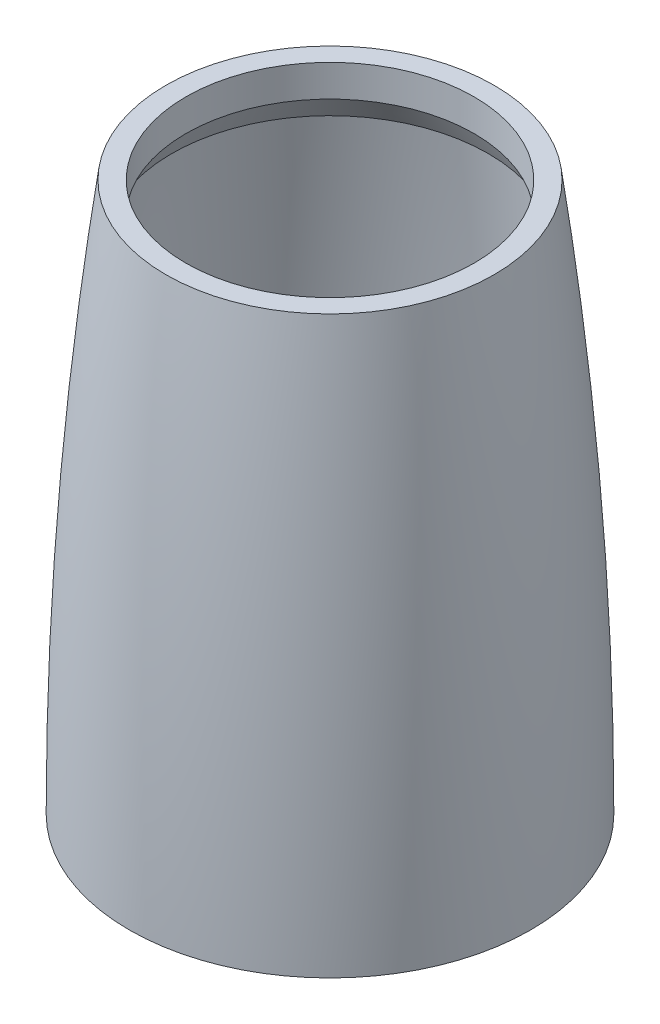
SolidWorks part; units mm, degrees
ref_plane "Front Plane" through (0, 0, 0) normal (0, 0, 1) x (1, 0, 0)
ref_plane "Top Plane" through (0, 0, 0) normal (0, 1, 0) x (1, 0, 0)
ref_plane "Right Plane" through (0, 0, 0) normal (1, 0, 0) x (0, 0, -1)
sketch "Sketch1" plane through (0, 0, 0) normal (1, 0, 0) x (0, 0, -1)
  line L0 (0, 0) -> (0, 323.85) construction
  line L2 (-51.054, 1000) -> (-51.054, 0) construction
  line L8 (0, 323.85) -> (0, 312.9504) construction
  line L9 (-41.743, 139.7) -> (-36.663, 139.7)
  line L10 (-36.663, 139.7) -> (-36.663, 131.6014)
  line L11 (-36.663, 131.6014) -> (-40.2294, 125.4241)
  line L15 (-47.7468, 3.302) -> (-22.6685, 3.302) construction
  line L16 (-22.6685, 3.302) -> (-22.7838, -64.8983) construction
  line L17 (-25.9761, 0) -> (-26.0858, -64.8927) construction
  line L18 (-45.72, 0) -> (-45.72, 10.16)
  line L19 (-45.72, 10.16) -> (-47.6935, 11.0803)
  line L20 (-51.054, 0) -> (-25.9761, 0) construction
  line L21 (-45.72, 0) -> (-51.054, 0)
  arc A2 (-51.054, 0) -> (-41.743, 139.7) centre (1001.6092, 0) cw
  arc A3 (-47.6935, 11.0803) -> (-40.2294, 125.4241) centre (1001.6092, 0) cw
  arc A4 (-47.7468, 3.302) -> (3.1419, 322.8341) centre (1001.6092, 0) cw construction
  arc A5 (-41.743, 139.7) -> (0, 323.85) centre (1001.6092, 0) cw construction
  arc A6 (-51.054, 0) -> (0, 323.85) centre (1001.6092, 0) cw construction
  arc A7 (-40.2294, 125.4241) -> (0, 312.9504) centre (1001.6092, 0) cw construction
  dimension "D6" = 139.7
  dimension "D1" = 323.85
  dimension "D2" = 5.334
  dimension "D3" = 51.054
  dimension "D4" = 10.16
  dimension "D5" = 3.302
  dimension "D7" = 5.08
  dimension "D8" = 8.0986
  dimension "D9" = 150
  dimension "D10" = 115
revolve "Revolve1" add sketch "Sketch1" angle 360 about L0
